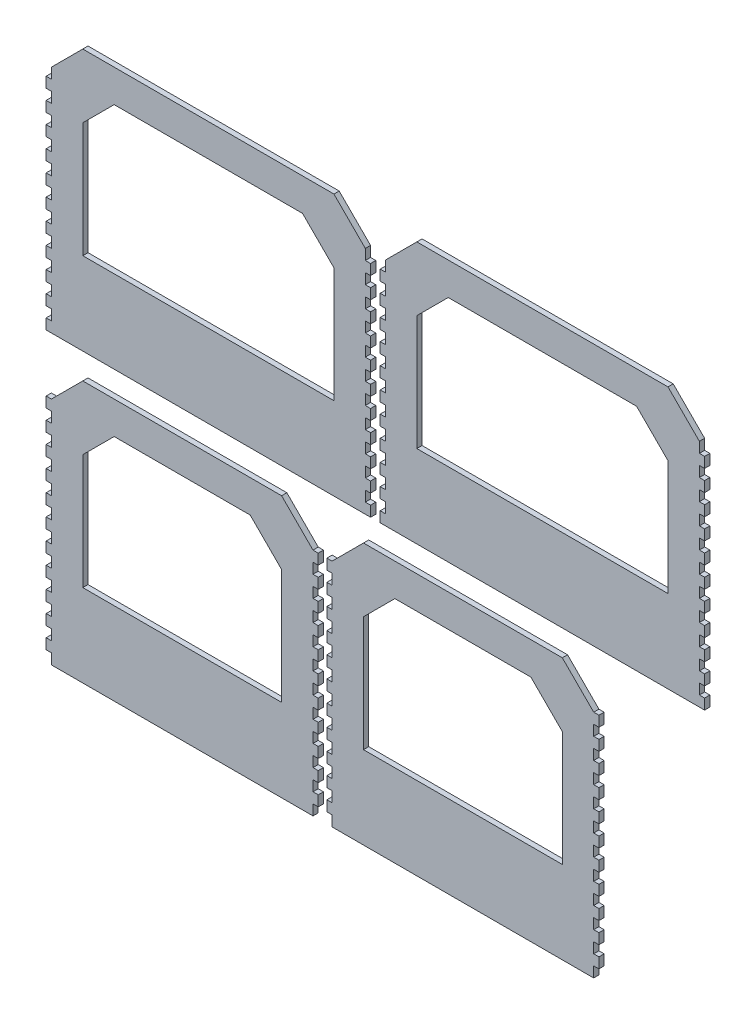
SolidWorks part; units mm, degrees
ref_plane "Ebene vorne" through (0, 0, 0) normal (0, 0, 1) x (1, 0, 0)
ref_plane "Ebene oben" through (0, 0, 0) normal (0, 1, 0) x (1, 0, 0)
ref_plane "Ebene rechts" through (0, 0, 0) normal (1, 0, 0) x (0, 0, -1)
sketch "Skizze1" plane through (0, 0, 0) normal (0, 0, 1) x (1, 0, 0)
  line L0 (430.8962, 326.3402) -> (430.8962, 336.3402)
  line L1 (430.8962, 316.3402) -> (730.8962, 316.3402)
  line L2 (730.8962, 326.3402) -> (730.8962, 336.3402)
  line L3 (460.8962, 566.3402) -> (700.8962, 566.3402)
  line L4 (430.8962, 536.3402) -> (460.8962, 566.3402)
  line L5 (730.8962, 536.3402) -> (700.8962, 566.3402)
  line L6 (700.8962, 505.3114) -> (670.8962, 535.3114)
  line L7 (460.8962, 395.3114) -> (700.8962, 395.3114)
  line L8 (460.8962, 395.3114) -> (460.8962, 505.3114)
  line L9 (490.8962, 535.3114) -> (670.8962, 535.3114)
  line L10 (700.8962, 395.3114) -> (700.8962, 505.3114)
  line L11 (460.8962, 505.3114) -> (490.8962, 535.3114)
  line L12 (1055.1294, 316.3402) -> (1055.1294, 326.3402)
  line L13 (730.8962, 316.3402) -> (735.8962, 316.3402)
  line L14 (735.8962, 316.3402) -> (735.8962, 326.3402)
  line L15 (735.8962, 326.3402) -> (730.8962, 326.3402)
  line L16 (730.8962, 346.3402) -> (730.8962, 356.3402)
  line L17 (730.8962, 336.3402) -> (735.8962, 336.3402)
  line L18 (735.8962, 336.3402) -> (735.8962, 346.3402)
  line L19 (735.8962, 346.3402) -> (730.8962, 346.3402)
  line L20 (730.8962, 366.3402) -> (730.8962, 376.3402)
  line L21 (730.8962, 356.3402) -> (735.8962, 356.3402)
  line L22 (735.8962, 356.3402) -> (735.8962, 366.3402)
  line L23 (735.8962, 366.3402) -> (730.8962, 366.3402)
  line L24 (730.8962, 386.3402) -> (730.8962, 396.3402)
  line L25 (730.8962, 376.3402) -> (735.8962, 376.3402)
  line L26 (735.8962, 376.3402) -> (735.8962, 386.3402)
  line L27 (735.8962, 386.3402) -> (730.8962, 386.3402)
  line L28 (730.8962, 406.3402) -> (730.8962, 416.3402)
  line L29 (730.8962, 396.3402) -> (735.8962, 396.3402)
  line L30 (735.8962, 396.3402) -> (735.8962, 406.3402)
  line L31 (735.8962, 406.3402) -> (730.8962, 406.3402)
  line L32 (730.8962, 426.3402) -> (730.8962, 436.3402)
  line L33 (730.8962, 416.3402) -> (735.8962, 416.3402)
  line L34 (735.8962, 416.3402) -> (735.8962, 426.3402)
  line L35 (735.8962, 426.3402) -> (730.8962, 426.3402)
  line L36 (730.8962, 446.3402) -> (730.8962, 456.3402)
  line L37 (730.8962, 436.3402) -> (735.8962, 436.3402)
  line L38 (735.8962, 436.3402) -> (735.8962, 446.3402)
  line L39 (735.8962, 446.3402) -> (730.8962, 446.3402)
  line L40 (730.8962, 466.3402) -> (730.8962, 476.3402)
  line L41 (730.8962, 456.3402) -> (735.8962, 456.3402)
  line L42 (735.8962, 456.3402) -> (735.8962, 466.3402)
  line L43 (735.8962, 466.3402) -> (730.8962, 466.3402)
  line L44 (730.8962, 486.3402) -> (730.8962, 496.3402)
  line L45 (730.8962, 476.3402) -> (735.8962, 476.3402)
  line L46 (735.8962, 476.3402) -> (735.8962, 486.3402)
  line L47 (735.8962, 486.3402) -> (730.8962, 486.3402)
  line L48 (730.8962, 506.3402) -> (730.8962, 516.3402)
  line L49 (730.8962, 496.3402) -> (735.8962, 496.3402)
  line L50 (735.8962, 496.3402) -> (735.8962, 506.3402)
  line L51 (735.8962, 506.3402) -> (730.8962, 506.3402)
  line L52 (730.8962, 526.3402) -> (730.8962, 536.3402)
  line L53 (730.8962, 516.3402) -> (735.8962, 516.3402)
  line L54 (735.8962, 516.3402) -> (735.8962, 526.3402)
  line L55 (735.8962, 526.3402) -> (730.8962, 526.3402)
  line L56 (430.8962, 316.3402) -> (425.8962, 316.3402)
  line L57 (425.8962, 316.3402) -> (425.8962, 326.3402)
  line L58 (425.8962, 326.3402) -> (430.8962, 326.3402)
  line L59 (430.8962, 346.3402) -> (430.8962, 356.3402)
  line L60 (425.8962, 336.3402) -> (425.8962, 346.3402)
  line L61 (425.8962, 346.3402) -> (430.8962, 346.3402)
  line L62 (430.8962, 366.3402) -> (430.8962, 376.3402)
  line L63 (425.8962, 356.3402) -> (425.8962, 366.3402)
  line L64 (425.8962, 366.3402) -> (430.8962, 366.3402)
  line L65 (430.8962, 386.3402) -> (430.8962, 396.3402)
  line L66 (425.8962, 376.3402) -> (425.8962, 386.3402)
  line L67 (425.8962, 386.3402) -> (430.8962, 386.3402)
  line L68 (430.8962, 406.3402) -> (430.8962, 416.3402)
  line L69 (425.8962, 396.3402) -> (425.8962, 406.3402)
  line L70 (425.8962, 406.3402) -> (430.8962, 406.3402)
  line L71 (430.8962, 426.3402) -> (430.8962, 436.3402)
  line L72 (425.8962, 416.3402) -> (425.8962, 426.3402)
  line L73 (425.8962, 426.3402) -> (430.8962, 426.3402)
  line L74 (430.8962, 446.3402) -> (430.8962, 456.3402)
  line L75 (425.8962, 436.3402) -> (425.8962, 446.3402)
  line L76 (425.8962, 446.3402) -> (430.8962, 446.3402)
  line L77 (430.8962, 466.3402) -> (430.8962, 476.3402)
  line L78 (425.8962, 456.3402) -> (425.8962, 466.3402)
  line L79 (425.8962, 466.3402) -> (430.8962, 466.3402)
  line L80 (430.8962, 486.3402) -> (430.8962, 496.3402)
  line L81 (425.8962, 476.3402) -> (425.8962, 486.3402)
  line L82 (425.8962, 486.3402) -> (430.8962, 486.3402)
  line L83 (430.8962, 506.3402) -> (430.8962, 516.3402)
  line L84 (425.8962, 496.3402) -> (425.8962, 506.3402)
  line L85 (425.8962, 506.3402) -> (430.8962, 506.3402)
  line L86 (430.8962, 526.3402) -> (430.8962, 536.3402)
  line L87 (425.8962, 516.3402) -> (425.8962, 526.3402)
  line L88 (425.8962, 526.3402) -> (430.8962, 526.3402)
  line L89 (425.8962, 336.3402) -> (430.8962, 336.3402)
  line L90 (425.8962, 356.3402) -> (430.8962, 356.3402)
  line L91 (425.8962, 376.3402) -> (430.8962, 376.3402)
  line L92 (425.8962, 396.3402) -> (430.8962, 396.3402)
  line L93 (425.8962, 416.3402) -> (430.8962, 416.3402)
  line L94 (425.8962, 436.3402) -> (430.8962, 436.3402)
  line L95 (425.8962, 456.3402) -> (430.8962, 456.3402)
  line L96 (425.8962, 476.3402) -> (430.8962, 476.3402)
  line L97 (425.8962, 496.3402) -> (430.8962, 496.3402)
  line L98 (425.8962, 516.3402) -> (430.8962, 516.3402)
  line L99 (1050.1294, 396.3402) -> (1055.1294, 396.3402)
  line L100 (1050.1294, 496.3402) -> (1055.1294, 496.3402)
  line L101 (745.1294, 356.3402) -> (745.1294, 366.3402)
  line L102 (745.1294, 376.3402) -> (750.1294, 376.3402)
  line L103 (745.1294, 456.3402) -> (750.1294, 456.3402)
  line L104 (1020.1294, 395.3114) -> (1020.1294, 505.3114)
  line L105 (1055.1294, 406.3402) -> (1050.1294, 406.3402)
  line L106 (1050.1294, 446.3402) -> (1050.1294, 456.3402)
  line L107 (750.1294, 346.3402) -> (750.1294, 356.3402)
  line L108 (745.1294, 526.3402) -> (750.1294, 526.3402)
  line L109 (745.1294, 436.3402) -> (750.1294, 436.3402)
  line L110 (810.1294, 535.3114) -> (990.1294, 535.3114)
  line L111 (1055.1294, 326.3402) -> (1050.1294, 326.3402)
  line L112 (1050.1294, 426.3402) -> (1050.1294, 436.3402)
  line L113 (1055.1294, 476.3402) -> (1055.1294, 486.3402)
  line L114 (745.1294, 396.3402) -> (745.1294, 406.3402)
  line L115 (750.1294, 486.3402) -> (750.1294, 496.3402)
  line L116 (745.1294, 506.3402) -> (750.1294, 506.3402)
  line L117 (1050.1294, 316.3402) -> (1055.1294, 316.3402)
  line L118 (1050.1294, 376.3402) -> (1055.1294, 376.3402)
  line L119 (1050.1294, 476.3402) -> (1055.1294, 476.3402)
  line L120 (745.1294, 446.3402) -> (750.1294, 446.3402)
  line L121 (750.1294, 506.3402) -> (750.1294, 516.3402)
  line L122 (745.1294, 396.3402) -> (750.1294, 396.3402)
  line L123 (1050.1294, 356.3402) -> (1055.1294, 356.3402)
  line L124 (1050.1294, 436.3402) -> (1055.1294, 436.3402)
  line L125 (1055.1294, 486.3402) -> (1050.1294, 486.3402)
  line L126 (1055.1294, 526.3402) -> (1050.1294, 526.3402)
  line L127 (750.1294, 386.3402) -> (750.1294, 396.3402)
  line L128 (750.1294, 536.3402) -> (780.1294, 566.3402)
  line L129 (1050.1294, 336.3402) -> (1055.1294, 336.3402)
  line L130 (1050.1294, 416.3402) -> (1055.1294, 416.3402)
  line L131 (745.1294, 366.3402) -> (750.1294, 366.3402)
  line L132 (745.1294, 456.3402) -> (745.1294, 466.3402)
  line L133 (745.1294, 466.3402) -> (750.1294, 466.3402)
  line L134 (1055.1294, 446.3402) -> (1050.1294, 446.3402)
  line L135 (1055.1294, 466.3402) -> (1050.1294, 466.3402)
  line L136 (1050.1294, 526.3402) -> (1050.1294, 536.3402)
  line L137 (750.1294, 366.3402) -> (750.1294, 376.3402)
  line L138 (745.1294, 476.3402) -> (750.1294, 476.3402)
  line L139 (1050.1294, 536.3402) -> (1020.1294, 566.3402)
  line L140 (1055.1294, 386.3402) -> (1050.1294, 386.3402)
  line L141 (1055.1294, 436.3402) -> (1055.1294, 446.3402)
  line L142 (745.1294, 346.3402) -> (750.1294, 346.3402)
  line L143 (750.1294, 426.3402) -> (750.1294, 436.3402)
  line L144 (780.1294, 566.3402) -> (1020.1294, 566.3402)
  line L145 (1055.1294, 416.3402) -> (1055.1294, 426.3402)
  line L146 (1055.1294, 506.3402) -> (1050.1294, 506.3402)
  line L147 (745.1294, 496.3402) -> (750.1294, 496.3402)
  line L148 (1050.1294, 346.3402) -> (1050.1294, 356.3402)
  line L149 (1055.1294, 366.3402) -> (1050.1294, 366.3402)
  line L150 (1055.1294, 376.3402) -> (1055.1294, 386.3402)
  line L151 (750.1294, 316.3402) -> (745.1294, 316.3402)
  line L152 (745.1294, 416.3402) -> (745.1294, 426.3402)
  line L153 (750.1294, 446.3402) -> (750.1294, 456.3402)
  line L154 (745.1294, 486.3402) -> (750.1294, 486.3402)
  line L155 (1055.1294, 356.3402) -> (1055.1294, 366.3402)
  line L156 (1050.1294, 386.3402) -> (1050.1294, 396.3402)
  line L157 (1055.1294, 426.3402) -> (1050.1294, 426.3402)
  line L158 (1055.1294, 496.3402) -> (1055.1294, 506.3402)
  line L159 (745.1294, 476.3402) -> (745.1294, 486.3402)
  line L160 (745.1294, 516.3402) -> (745.1294, 526.3402)
  line L161 (1050.1294, 326.3402) -> (1050.1294, 336.3402)
  line L162 (1020.1294, 505.3114) -> (990.1294, 535.3114)
  line L163 (1050.1294, 466.3402) -> (1050.1294, 476.3402)
  line L164 (1050.1294, 516.3402) -> (1055.1294, 516.3402)
  line L165 (745.1294, 386.3402) -> (750.1294, 386.3402)
  line L166 (750.1294, 406.3402) -> (750.1294, 416.3402)
  line L167 (780.1294, 395.3114) -> (1020.1294, 395.3114)
  line L168 (1055.1294, 336.3402) -> (1055.1294, 346.3402)
  line L169 (1050.1294, 406.3402) -> (1050.1294, 416.3402)
  line L170 (745.1294, 326.3402) -> (750.1294, 326.3402)
  line L171 (745.1294, 376.3402) -> (745.1294, 386.3402)
  line L172 (745.1294, 496.3402) -> (745.1294, 506.3402)
  line L173 (745.1294, 336.3402) -> (750.1294, 336.3402)
  line L174 (750.1294, 326.3402) -> (750.1294, 336.3402)
  line L175 (1055.1294, 346.3402) -> (1050.1294, 346.3402)
  line L176 (1055.1294, 456.3402) -> (1055.1294, 466.3402)
  line L177 (745.1294, 406.3402) -> (750.1294, 406.3402)
  line L178 (750.1294, 316.3402) -> (1050.1294, 316.3402)
  line L179 (780.1294, 505.3114) -> (810.1294, 535.3114)
  line L180 (745.1294, 316.3402) -> (745.1294, 326.3402)
  line L181 (745.1294, 336.3402) -> (745.1294, 346.3402)
  line L182 (745.1294, 436.3402) -> (745.1294, 446.3402)
  line L183 (750.1294, 466.3402) -> (750.1294, 476.3402)
  line L184 (745.1294, 356.3402) -> (750.1294, 356.3402)
  line L185 (1055.1294, 396.3402) -> (1055.1294, 406.3402)
  line L186 (1050.1294, 456.3402) -> (1055.1294, 456.3402)
  line L187 (1055.1294, 516.3402) -> (1055.1294, 526.3402)
  line L188 (750.1294, 526.3402) -> (750.1294, 536.3402)
  line L189 (745.1294, 416.3402) -> (750.1294, 416.3402)
  line L190 (780.1294, 395.3114) -> (780.1294, 505.3114)
  line L191 (1050.1294, 366.3402) -> (1050.1294, 376.3402)
  line L192 (1050.1294, 486.3402) -> (1050.1294, 496.3402)
  line L193 (1050.1294, 506.3402) -> (1050.1294, 516.3402)
  line L194 (745.1294, 426.3402) -> (750.1294, 426.3402)
  line L195 (745.1294, 516.3402) -> (750.1294, 516.3402)
  line L196 (460.8962, 291.6639) -> (650.8962, 291.6639)
  line L197 (680.8962, 261.6639) -> (685.8962, 261.6639)
  line L198 (685.8962, 261.6639) -> (685.8962, 251.6639)
  line L199 (430.8962, 231.6639) -> (430.8962, 221.6639)
  line L200 (490.8962, 260.635) -> (620.8962, 260.635)
  line L201 (680.8962, 251.6639) -> (680.8962, 241.6639)
  line L202 (680.8962, 241.6639) -> (685.8962, 241.6639)
  line L203 (685.8962, 241.6639) -> (685.8962, 231.6639)
  line L204 (430.8962, 241.6639) -> (425.8962, 241.6639)
  line L205 (430.8962, 251.6639) -> (430.8962, 241.6639)
  line L206 (425.8962, 231.6639) -> (430.8962, 231.6639)
  line L207 (460.8962, 120.635) -> (460.8962, 230.635)
  line L208 (680.8962, 231.6639) -> (680.8962, 221.6639)
  line L209 (685.8962, 231.6639) -> (680.8962, 231.6639)
  line L210 (425.8962, 241.6639) -> (425.8962, 231.6639)
  line L211 (430.8962, 211.6639) -> (430.8962, 201.6639)
  line L212 (430.8962, 221.6639) -> (425.8962, 221.6639)
  line L213 (425.8962, 211.6639) -> (430.8962, 211.6639)
  line L214 (430.8962, 261.6639) -> (460.8962, 291.6639)
  line L215 (680.8962, 221.6639) -> (685.8962, 221.6639)
  line L216 (685.8962, 221.6639) -> (685.8962, 211.6639)
  line L217 (680.8962, 211.6639) -> (680.8962, 201.6639)
  line L218 (425.8962, 221.6639) -> (425.8962, 211.6639)
  line L219 (430.8962, 261.6639) -> (425.8962, 261.6639)
  line L220 (685.8962, 211.6639) -> (680.8962, 211.6639)
  line L221 (680.8962, 201.6639) -> (685.8962, 201.6639)
  line L222 (430.8962, 191.6639) -> (430.8962, 181.6639)
  line L223 (430.8962, 201.6639) -> (425.8962, 201.6639)
  line L224 (650.8962, 230.635) -> (620.8962, 260.635)
  line L225 (685.8962, 201.6639) -> (685.8962, 191.6639)
  line L226 (680.8962, 191.6639) -> (680.8962, 181.6639)
  line L227 (685.8962, 191.6639) -> (680.8962, 191.6639)
  line L228 (425.8962, 191.6639) -> (430.8962, 191.6639)
  line L229 (425.8962, 201.6639) -> (425.8962, 191.6639)
  line L230 (680.8962, 181.6639) -> (685.8962, 181.6639)
  line L231 (685.8962, 181.6639) -> (685.8962, 171.6639)
  line L232 (685.8962, 251.6639) -> (680.8962, 251.6639)
  line L233 (430.8962, 171.6639) -> (430.8962, 161.6639)
  line L234 (430.8962, 181.6639) -> (425.8962, 181.6639)
  line L235 (425.8962, 251.6639) -> (430.8962, 251.6639)
  line L236 (425.8962, 171.6639) -> (430.8962, 171.6639)
  line L237 (680.8962, 171.6639) -> (680.8962, 161.6639)
  line L238 (425.8962, 181.6639) -> (425.8962, 171.6639)
  line L239 (430.8962, 151.6639) -> (430.8962, 141.6639)
  line L240 (430.8962, 161.6639) -> (425.8962, 161.6639)
  line L241 (460.8962, 120.635) -> (650.8962, 120.635)
  line L242 (685.8962, 171.6639) -> (680.8962, 171.6639)
  line L243 (680.8962, 161.6639) -> (685.8962, 161.6639)
  line L244 (685.8962, 161.6639) -> (685.8962, 151.6639)
  line L245 (680.8962, 151.6639) -> (680.8962, 141.6639)
  line L246 (685.8962, 151.6639) -> (680.8962, 151.6639)
  line L247 (425.8962, 151.6639) -> (430.8962, 151.6639)
  line L248 (425.8962, 161.6639) -> (425.8962, 151.6639)
  line L249 (430.8962, 131.6639) -> (430.8962, 121.6639)
  line L250 (430.8962, 141.6639) -> (425.8962, 141.6639)
  line L251 (425.8962, 131.6639) -> (430.8962, 131.6639)
  line L252 (430.8962, 41.6639) -> (680.8962, 41.6639)
  line L253 (460.8962, 230.635) -> (490.8962, 260.635)
  line L254 (680.8962, 141.6639) -> (685.8962, 141.6639)
  line L255 (685.8962, 141.6639) -> (685.8962, 131.6639)
  line L256 (680.8962, 131.6639) -> (680.8962, 121.6639)
  line L257 (685.8962, 131.6639) -> (680.8962, 131.6639)
  line L258 (680.8962, 121.6639) -> (685.8962, 121.6639)
  line L259 (685.8962, 121.6639) -> (685.8962, 111.6639)
  line L260 (425.8962, 141.6639) -> (425.8962, 131.6639)
  line L261 (430.8962, 111.6639) -> (430.8962, 101.6639)
  line L262 (680.8962, 111.6639) -> (680.8962, 101.6639)
  line L263 (650.8962, 120.635) -> (650.8962, 230.635)
  line L264 (685.8962, 111.6639) -> (680.8962, 111.6639)
  line L265 (430.8962, 121.6639) -> (425.8962, 121.6639)
  line L266 (425.8962, 111.6639) -> (430.8962, 111.6639)
  line L267 (425.8962, 121.6639) -> (425.8962, 111.6639)
  line L268 (430.8962, 91.6639) -> (430.8962, 81.6639)
  line L269 (680.8962, 101.6639) -> (685.8962, 101.6639)
  line L270 (685.8962, 101.6639) -> (685.8962, 91.6639)
  line L271 (680.8962, 91.6639) -> (680.8962, 81.6639)
  line L272 (430.8962, 101.6639) -> (425.8962, 101.6639)
  line L273 (425.8962, 91.6639) -> (430.8962, 91.6639)
  line L274 (680.8962, 261.6639) -> (650.8962, 291.6639)
  line L275 (685.8962, 91.6639) -> (680.8962, 91.6639)
  line L276 (680.8962, 81.6639) -> (685.8962, 81.6639)
  line L277 (425.8962, 101.6639) -> (425.8962, 91.6639)
  line L278 (430.8962, 71.6639) -> (430.8962, 61.6639)
  line L279 (425.8962, 261.6639) -> (425.8962, 251.6639)
  line L280 (430.8962, 81.6639) -> (425.8962, 81.6639)
  line L281 (685.8962, 81.6639) -> (685.8962, 71.6639)
  line L282 (680.8962, 71.6639) -> (680.8962, 61.6639)
  line L283 (685.8962, 71.6639) -> (680.8962, 71.6639)
  line L284 (680.8962, 61.6639) -> (685.8962, 61.6639)
  line L285 (685.8962, 61.6639) -> (685.8962, 51.6639)
  line L286 (425.8962, 71.6639) -> (430.8962, 71.6639)
  line L287 (680.8962, 51.6639) -> (680.8962, 41.6639)
  line L288 (685.8962, 51.6639) -> (680.8962, 51.6639)
  line L289 (425.8962, 81.6639) -> (425.8962, 71.6639)
  line L290 (430.8962, 51.6639) -> (430.8962, 41.6639)
  line L291 (430.8962, 61.6639) -> (425.8962, 61.6639)
  line L292 (425.8962, 51.6639) -> (430.8962, 51.6639)
  line L293 (425.8962, 61.6639) -> (425.8962, 51.6639)
  line L294 (954.1447, 261.6639) -> (954.1447, 251.6639)
  line L295 (954.1447, 221.6639) -> (954.1447, 211.6639)
  line L296 (694.1447, 171.6639) -> (699.1447, 171.6639)
  line L297 (949.1447, 121.6639) -> (954.1447, 121.6639)
  line L298 (699.1447, 121.6639) -> (694.1447, 121.6639)
  line L299 (954.1447, 51.6639) -> (949.1447, 51.6639)
  line L300 (729.1447, 291.6639) -> (919.1447, 291.6639)
  line L301 (949.1447, 261.6639) -> (954.1447, 261.6639)
  line L302 (699.1447, 251.6639) -> (699.1447, 241.6639)
  line L303 (729.1447, 120.635) -> (729.1447, 230.635)
  line L304 (949.1447, 171.6639) -> (949.1447, 161.6639)
  line L305 (954.1447, 171.6639) -> (949.1447, 171.6639)
  line L306 (949.1447, 141.6639) -> (954.1447, 141.6639)
  line L307 (954.1447, 231.6639) -> (949.1447, 231.6639)
  line L308 (954.1447, 251.6639) -> (949.1447, 251.6639)
  line L309 (699.1447, 181.6639) -> (694.1447, 181.6639)
  line L310 (699.1447, 91.6639) -> (699.1447, 81.6639)
  line L311 (954.1447, 81.6639) -> (954.1447, 71.6639)
  line L312 (954.1447, 61.6639) -> (954.1447, 51.6639)
  line L313 (694.1447, 51.6639) -> (699.1447, 51.6639)
  line L314 (954.1447, 241.6639) -> (954.1447, 231.6639)
  line L315 (699.1447, 261.6639) -> (694.1447, 261.6639)
  line L316 (954.1447, 181.6639) -> (954.1447, 171.6639)
  line L317 (694.1447, 131.6639) -> (699.1447, 131.6639)
  line L318 (949.1447, 131.6639) -> (949.1447, 121.6639)
  line L319 (694.1447, 101.6639) -> (694.1447, 91.6639)
  line L320 (694.1447, 231.6639) -> (699.1447, 231.6639)
  line L321 (694.1447, 211.6639) -> (699.1447, 211.6639)
  line L322 (954.1447, 211.6639) -> (949.1447, 211.6639)
  line L323 (699.1447, 191.6639) -> (699.1447, 181.6639)
  line L324 (919.1447, 120.635) -> (919.1447, 230.635)
  line L325 (699.1447, 71.6639) -> (699.1447, 61.6639)
  line L326 (694.1447, 261.6639) -> (694.1447, 251.6639)
  line L327 (949.1447, 241.6639) -> (954.1447, 241.6639)
  line L328 (699.1447, 221.6639) -> (694.1447, 221.6639)
  line L329 (694.1447, 151.6639) -> (699.1447, 151.6639)
  line L330 (954.1447, 141.6639) -> (954.1447, 131.6639)
  line L331 (694.1447, 111.6639) -> (699.1447, 111.6639)
  line L332 (694.1447, 91.6639) -> (699.1447, 91.6639)
  line L333 (949.1447, 261.6639) -> (919.1447, 291.6639)
  line L334 (949.1447, 231.6639) -> (949.1447, 221.6639)
  line L335 (699.1447, 211.6639) -> (699.1447, 201.6639)
  line L336 (699.1447, 161.6639) -> (694.1447, 161.6639)
  line L337 (694.1447, 141.6639) -> (694.1447, 131.6639)
  line L338 (949.1447, 71.6639) -> (949.1447, 61.6639)
  line L339 (694.1447, 81.6639) -> (694.1447, 71.6639)
  line L340 (694.1447, 241.6639) -> (694.1447, 231.6639)
  line L341 (699.1447, 201.6639) -> (694.1447, 201.6639)
  line L342 (694.1447, 181.6639) -> (694.1447, 171.6639)
  line L343 (949.1447, 101.6639) -> (954.1447, 101.6639)
  line L344 (949.1447, 221.6639) -> (954.1447, 221.6639)
  line L345 (949.1447, 191.6639) -> (949.1447, 181.6639)
  line L346 (694.1447, 201.6639) -> (694.1447, 191.6639)
  line L347 (699.1447, 141.6639) -> (694.1447, 141.6639)
  line L348 (699.1447, 81.6639) -> (694.1447, 81.6639)
  line L349 (699.1447, 261.6639) -> (729.1447, 291.6639)
  line L350 (694.1447, 191.6639) -> (699.1447, 191.6639)
  line L351 (949.1447, 161.6639) -> (954.1447, 161.6639)
  line L352 (699.1447, 111.6639) -> (699.1447, 101.6639)
  line L353 (954.1447, 91.6639) -> (949.1447, 91.6639)
  line L354 (954.1447, 71.6639) -> (949.1447, 71.6639)
  line L355 (699.1447, 231.6639) -> (699.1447, 221.6639)
  line L356 (954.1447, 191.6639) -> (949.1447, 191.6639)
  line L357 (699.1447, 151.6639) -> (699.1447, 141.6639)
  line L358 (699.1447, 131.6639) -> (699.1447, 121.6639)
  line L359 (949.1447, 91.6639) -> (949.1447, 81.6639)
  line L360 (694.1447, 71.6639) -> (699.1447, 71.6639)
  line L361 (919.1447, 230.635) -> (889.1447, 260.635)
  line L362 (949.1447, 151.6639) -> (949.1447, 141.6639)
  line L363 (954.1447, 151.6639) -> (949.1447, 151.6639)
  line L364 (699.1447, 51.6639) -> (699.1447, 41.6639)
  line L365 (699.1447, 61.6639) -> (694.1447, 61.6639)
  line L366 (949.1447, 181.6639) -> (954.1447, 181.6639)
  line L367 (729.1447, 230.635) -> (759.1447, 260.635)
  line L368 (954.1447, 131.6639) -> (949.1447, 131.6639)
  line L369 (954.1447, 101.6639) -> (954.1447, 91.6639)
  line L370 (949.1447, 51.6639) -> (949.1447, 41.6639)
  line L371 (694.1447, 61.6639) -> (694.1447, 51.6639)
  line L372 (699.1447, 171.6639) -> (699.1447, 161.6639)
  line L373 (694.1447, 161.6639) -> (694.1447, 151.6639)
  line L374 (699.1447, 41.6639) -> (949.1447, 41.6639)
  line L375 (949.1447, 61.6639) -> (954.1447, 61.6639)
  line L376 (949.1447, 201.6639) -> (954.1447, 201.6639)
  line L377 (954.1447, 201.6639) -> (954.1447, 191.6639)
  line L378 (694.1447, 251.6639) -> (699.1447, 251.6639)
  line L379 (694.1447, 121.6639) -> (694.1447, 111.6639)
  line L380 (759.1447, 260.635) -> (889.1447, 260.635)
  line L381 (949.1447, 251.6639) -> (949.1447, 241.6639)
  line L382 (699.1447, 241.6639) -> (694.1447, 241.6639)
  line L383 (694.1447, 221.6639) -> (694.1447, 211.6639)
  line L384 (729.1447, 120.635) -> (919.1447, 120.635)
  line L385 (954.1447, 161.6639) -> (954.1447, 151.6639)
  line L386 (699.1447, 101.6639) -> (694.1447, 101.6639)
  line L387 (949.1447, 81.6639) -> (954.1447, 81.6639)
  line L388 (949.1447, 211.6639) -> (949.1447, 201.6639)
  line L389 (954.1447, 121.6639) -> (954.1447, 111.6639)
  line L390 (949.1447, 111.6639) -> (949.1447, 101.6639)
  line L391 (954.1447, 111.6639) -> (949.1447, 111.6639)
extrude "Aufsatz-Linear austragen9" add sketch "Skizze1" along normal blind 5
